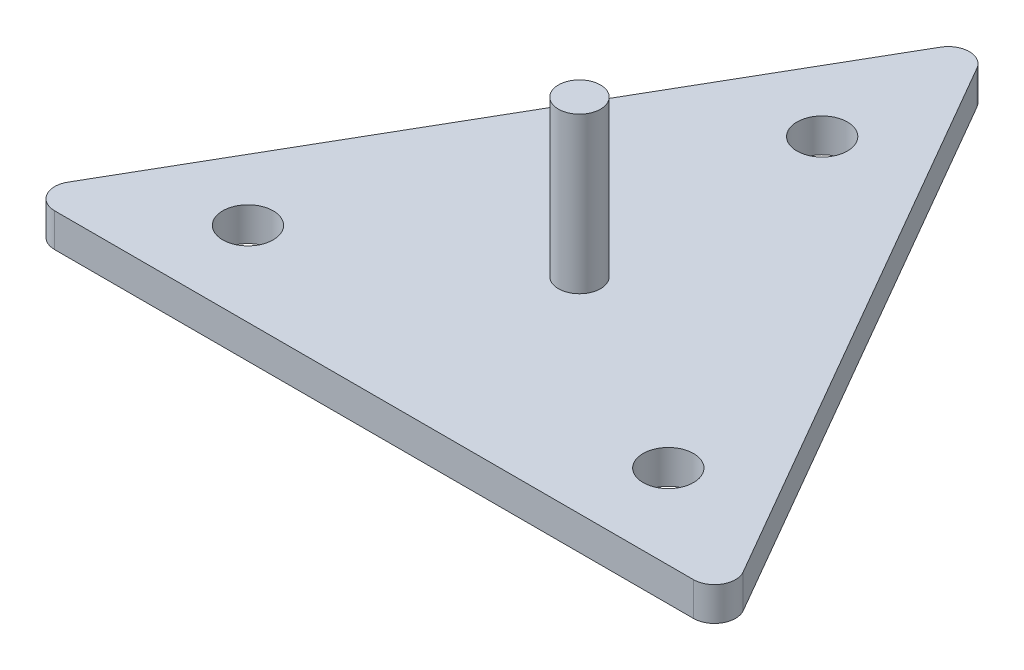
SolidWorks part; units mm, degrees
ref_plane "Front Plane" through (0, 0, 0) normal (0, 0, 1) x (1, 0, 0)
ref_plane "Top Plane" through (0, 0, 0) normal (0, 1, 0) x (1, 0, 0)
ref_plane "Right Plane" through (0, 0, 0) normal (1, 0, 0) x (0, 0, -1)
sketch "Sketch1" plane through (0, 0, 0) normal (0, 1, 0) x (1, 0, 0)
  line L0 (-115.6863, 120.509) -> (-65.6863, 207.1115)
  line L1 (-65.6863, 207.1115) -> (-15.6863, 120.509)
  line L2 (-15.6863, 120.509) -> (-115.6863, 120.509)
  line L3 (-65.6863, 247.1115) -> (18.9547, 100.509)
  line L4 (18.9547, 100.509) -> (-150.3273, 100.509)
  line L5 (-150.3273, 100.509) -> (-65.6863, 247.1115)
  dimension "D1" = 100
  dimension "D2" = 20
extrude "Boss-Extrude1" add sketch "Sketch1" along normal blind 8 contours L3 L4 L5
sketch "Sketch4" plane through (0, 8, 0) normal (0, 1, 0) x (1, 0, 0)
  line L6 (-65.6863, 207.1115) -> (-115.6863, 120.509)
  line L7 (-115.6863, 120.509) -> (-15.6863, 120.509)
  line L8 (-15.6863, 120.509) -> (-65.6863, 207.1115)
  line L9 (-65.6863, 207.1115) -> (-115.6863, 120.509)
  line L10 (-115.6863, 120.509) -> (-15.6863, 120.509)
  line L11 (-15.6863, 120.509) -> (-65.6863, 207.1115)
  dimension "D1" = 20
hole_wizard "Ø12.0 (12) Diameter Hole1" positions "Sketch5" profile "Sketch7" hole size "Ø12.0" standard "ISO" end condition through all
sketch "Sketch5" plane through (0, 8, 0) normal (0, 1, 0) x (1, 0, 0)
  point P0 (-65.6863, 207.1115)
  point P3 (-115.6863, 120.509)
  point P6 (-15.6863, 120.509)
sketch "Sketch7" plane through (-65.6863, 8, -207.1115) normal (1, 0, 0) x (0, 0, 1)
  line L0 (0, 0) -> (0, 8)
  line L1 (0, 8) -> (6, 8)
  line L2 (6, 8) -> (6, 0)
  line L5 (6, 0) -> (0, 0)
  line L11 (0, -6.35) -> (0, 107.95) construction
  dimension "Thru Hole Dia." = 12
  dimension "Thru Hole Depth" = 8
sketch "Sketch8" plane through (0, 0, 0) normal (0, -1, 0) x (-1, 0, 0)
  circle A0 centre (65.6863, 149.3765) radius 97.735 construction
  circle A1 centre (65.6863, 149.3765) radius 5
extrude "Boss-Extrude2" add sketch "Sketch8" against normal blind 45
fillet "Fillet1" radius 5 3 edges at (-150.3273, 4, -100.509) (-65.6863, 4, -247.1115) (18.9547, 4, -100.509)
equation "\"TRIANGLE_SIDE\"= 100"
equation "\"D1@Sketch1\"=\"TRIANGLE_SIDE\""
equation "\"TRIANGLE_OFFSET\"=20"
equation "\"D2@Sketch1\"=\"TRIANGLE_OFFSET\""
equation "\"TRIANGLE_Z\"= 8"
equation "\"D1@Boss-Extrude1\"=\"TRIANGLE_Z\""
equation "\"D1@Sketch4\"=\"TRIANGLE_OFFSET\""
